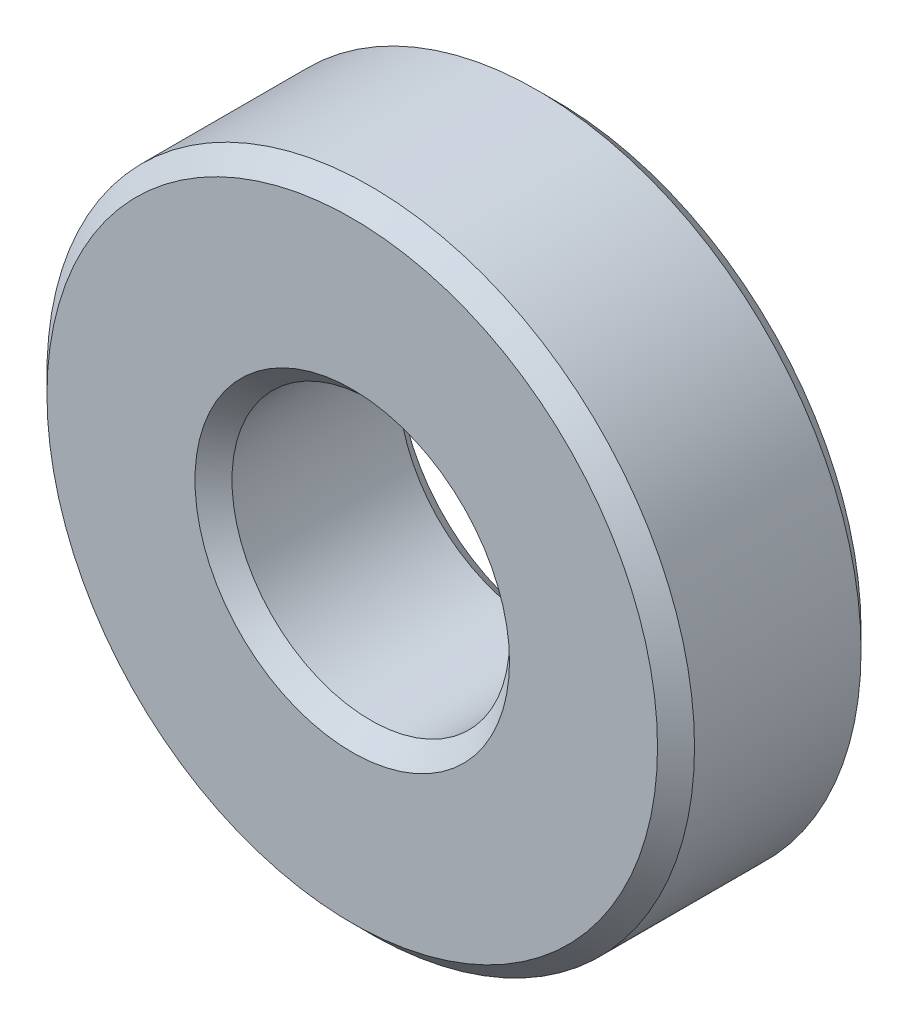
SolidWorks part; units mm, degrees
ref_plane "前视基准面" through (0, 0, 0) normal (0, 0, 1) x (1, 0, 0)
ref_plane "上视基准面" through (0, 0, 0) normal (0, 1, 0) x (1, 0, 0)
ref_plane "右视基准面" through (0, 0, 0) normal (1, 0, 0) x (0, 0, -1)
sketch "草图1" plane through (0, 0, 0) normal (0, 0, 1) x (1, 0, 0)
  circle A0 centre (0, 0) radius 17.5
  circle A1 centre (0, 0) radius 7.5
extrude "凸台-拉伸1" add sketch "草图1" along normal blind 11
chamfer "倒角1" distance 1 angle 45 4 edges at (7.5, 0, 0) (17.5, 0, 0) (7.5, 0, 11) (17.5, 0, 11)
